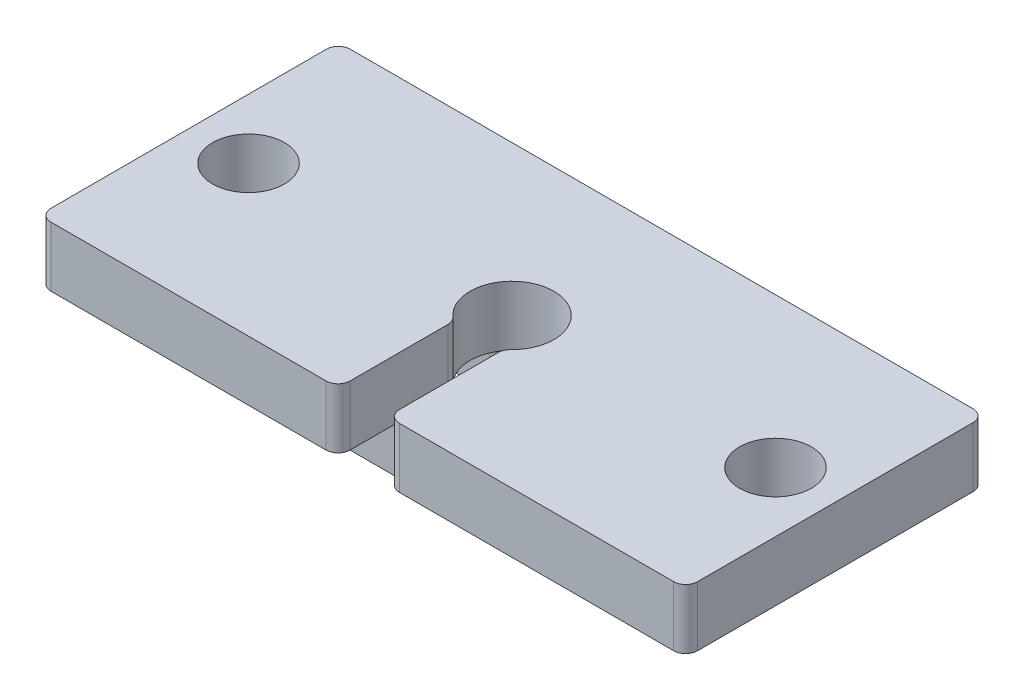
SolidWorks part; units mm, degrees
ref_plane "Front Plane" through (0, 0, 0) normal (0, 0, 1) x (1, 0, 0)
ref_plane "Top Plane" through (0, 0, 0) normal (0, 1, 0) x (1, 0, 0)
ref_plane "Right Plane" through (0, 0, 0) normal (1, 0, 0) x (0, 0, -1)
sketch "Sketch1" plane through (0, 0, 0) normal (0, 1, 0) x (1, 0, 0)
  line L0 (-27.2141, 1.8927) -> (26.7859, 1.8927) construction
  line L1 (-26.2141, 14.3927) -> (25.7859, 14.3927)
  line L2 (-27.2141, 13.3927) -> (-27.2141, -9.6073)
  line L3 (-26.2141, -10.6073) -> (-3.237, -10.6073)
  line L4 (26.7859, 13.3927) -> (26.7859, -9.6073)
  line L5 (-2.237, -1.4408) -> (-2.237, -9.6073)
  line L6 (1.8931, -1.3623) -> (1.8931, -9.6073)
  line L7 (2.8931, -10.6073) -> (25.7859, -10.6073)
  circle A0 centre (-22.2141, 1.8927) radius 3
  circle A1 centre (21.7859, 1.8927) radius 3
  arc A3 (-2.5652, -0.7) -> (2.2026, -0.639) centre (-0.2141, 1.8927) cw
  arc A4 (-2.237, -9.6073) -> (-3.237, -10.6073) centre (-3.237, -9.6073) cw
  arc A5 (2.8931, -10.6073) -> (1.8931, -9.6073) centre (2.8931, -9.6073) cw
  arc A6 (-2.237, -1.4408) -> (-2.5652, -0.7) centre (-3.237, -1.4408) ccw
  arc A7 (1.8931, -1.3623) -> (2.2026, -0.639) centre (2.8931, -1.3623) cw
  arc A8 (25.7859, -10.6073) -> (26.7859, -9.6073) centre (25.7859, -9.6073) ccw
  arc A9 (26.7859, 13.3927) -> (25.7859, 14.3927) centre (25.7859, 13.3927) ccw
  arc A10 (-26.2141, -10.6073) -> (-27.2141, -9.6073) centre (-26.2141, -9.6073) cw
  arc A11 (-27.2141, 13.3927) -> (-26.2141, 14.3927) centre (-26.2141, 13.3927) cw
  point P19 (1.8931, -10.6073)
  point P26 (26.7859, -10.6073)
  point P29 (26.7859, 14.3927)
  point P34 (-27.2141, 14.3927)
  dimension "D3" = 44
  dimension "D5" = 1
  dimension "D6" = 1
  dimension "D7" = 1
  dimension "D8" = 1
  dimension "D9" = 1
  dimension "D1" = 54
  dimension "D2" = 25
  dimension "D4" = 5
extrude "Boss-Extrude1" add sketch "Sketch1" along normal blind 5
sketch3d "3DSketch1"
  line L0 (26.7859, 0, 9.6073) -> (26.7859, 0, -13.3927) construction
  line L5 (25.7859, 0, -14.3927) -> (-26.2141, 0, -14.3927) construction
  line L6 (4.2454, 0, -4.8927) -> (4.2454, 0, -5.8927)
  line L7 (16.5434, 0, -4.3927) -> (4.7454, 0, -4.3927)
  line L8 (16.7859, 0, -9.1503) -> (16.7859, 0, -4.6352)
  line L9 (16.5434, 0, -9.3927) -> (-16.9717, 0, -9.3927)
  line L10 (-17.2141, 0, -9.1503) -> (-17.2141, 0, -4.6352)
  line L14 (-16.9717, 0, -4.3927) -> (-4.5831, 0, -4.3927)
  line L15 (-4.0831, 0, -4.8927) -> (-4.0831, 0, -5.8927)
  line L16 (3.7454, 0, -6.3927) -> (-3.5831, 0, -6.3927)
  line L17 (16.5434, 0, 0.6073) -> (4.2859, 0, 0.6073)
  line L18 (16.7859, 0, 0.8497) -> (16.7859, 0, 5.3648)
  line L20 (-17.2141, 0, 0.8497) -> (-17.2141, 0, 5.3648)
  line L21 (16.5434, 0, 5.6073) -> (2.1355, 0, 5.6073)
  line L22 (3.7859, 0, 1.1073) -> (3.7859, 0, 1.8648)
  line L23 (3.5434, 0, 2.1073) -> (2.3931, 0, 2.1073)
  line L24 (1.8931, 0, 1.3623) -> (1.8931, 0, 9.6073) construction
  line L25 (1.8931, 0, 2.6073) -> (1.8931, 0, 5.3648)
  line L26 (-16.9717, 0, 0.6073) -> (-4.7141, 0, 0.6073)
  line L27 (-4.2141, 0, 1.1073) -> (-4.2141, 0, 1.8648)
  line L28 (-3.9717, 0, 2.1073) -> (-2.737, 0, 2.1073)
  line L29 (-2.237, 0, 9.6073) -> (-2.237, 0, 1.4408) construction
  line L30 (-27.2141, 0, -13.3927) -> (-27.2141, 0, 9.6073) construction
  line L31 (-2.237, 0, 2.6073) -> (-2.237, 0, 5.3648)
  line L32 (-2.4794, 0, 5.6073) -> (-16.9717, 0, 5.6073)
  arc A0 (3.7454, 0, -6.3927) -> (4.2454, 0, -5.8927) centre (3.7454, 0, -5.8927) ccw
  arc A1 (-4.0831, 0, -5.8927) -> (-3.5831, 0, -6.3927) centre (-3.5831, 0, -5.8927) ccw
  arc A2 (-4.5831, 0, -4.3927) -> (-4.0831, 0, -4.8927) centre (-4.5831, 0, -4.8927) ccw
  arc A3 (4.7454, 0, -4.3927) -> (4.2454, 0, -4.8927) centre (4.7454, 0, -4.8927) ccw
  arc A4 (3.7859, 0, 1.1073) -> (4.2859, 0, 0.6073) centre (4.2859, 0, 1.1073) ccw
  arc A5 (1.8931, 0, 2.6073) -> (2.3931, 0, 2.1073) centre (2.3931, 0, 2.6073) ccw
  arc A6 (-2.237, 0, 2.6073) -> (-2.737, 0, 2.1073) centre (-2.737, 0, 2.6073) ccw
  arc A7 (-4.7141, 0, 0.6073) -> (-4.2141, 0, 1.1073) centre (-4.7141, 0, 1.1073) ccw
  arc A8 (-2.237, 0, 5.3648) -> (-2.4794, 0, 5.6073) centre (-2.4794, 0, 5.3648) ccw
  arc A9 (1.8931, 0, 5.3648) -> (2.1355, 0, 5.6073) centre (2.1355, 0, 5.3648) ccw
  arc A10 (16.7859, 0, -9.1503) -> (16.5434, 0, -9.3927) centre (16.5434, 0, -9.1503) ccw
  arc A11 (16.5434, 0, -4.3927) -> (16.7859, 0, -4.6352) centre (16.5434, 0, -4.6352) ccw
  arc A12 (-17.2141, 0, -9.1503) -> (-16.9717, 0, -9.3927) centre (-16.9717, 0, -9.1503) ccw
  arc A13 (-16.9717, 0, -4.3927) -> (-17.2141, 0, -4.6352) centre (-16.9717, 0, -4.6352) ccw
  arc A14 (-17.2141, 0, 0.8497) -> (-16.9717, 0, 0.6073) centre (-16.9717, 0, 0.8497) ccw
  arc A15 (-16.9717, 0, 5.6073) -> (-17.2141, 0, 5.3648) centre (-16.9717, 0, 5.3648) ccw
  arc A16 (16.7859, 0, 5.3648) -> (16.5434, 0, 5.6073) centre (16.5434, 0, 5.3648) ccw
  arc A17 (16.7859, 0, 0.8497) -> (16.5434, 0, 0.6073) centre (16.5434, 0, 0.8497) ccw
  arc A18 (3.5434, 0, 2.1073) -> (3.7859, 0, 1.8648) centre (3.5434, 0, 1.8648) ccw
  arc A19 (-3.9717, 0, 2.1073) -> (-4.2141, 0, 1.8648) centre (-3.9717, 0, 1.8648) ccw
  point P14 (4.2454, 0, -6.3927)
  point P15 (3.7454, -0.5, -5.8927)
  point P18 (-4.0831, 0, -6.3927)
  point P19 (-3.5831, -0.5, -5.8927)
  point P22 (-4.0831, 0, -4.3927)
  point P23 (-4.5831, 0.5, -4.8927)
  point P26 (4.2454, 0, -4.3927)
  point P27 (4.7454, -0.5, -4.8927)
  point P48 (3.7859, 0, 0.6073)
  point P49 (4.2859, -0.5, 1.1073)
  point P52 (1.8931, 0, 2.1073)
  point P53 (2.3931, -0.5, 2.6073)
  point P56 (-2.237, 0, 2.1073)
  point P57 (-2.737, 0.5, 2.6073)
  point P60 (-4.2141, 0, 0.6073)
  point P61 (-4.7141, -0.5, 1.1073)
  point P64 (-2.237, 0, 5.6073)
  point P65 (-2.4794, -0.2424, 5.3648)
  point P68 (1.8931, 0, 5.6073)
  point P69 (2.1355, 0.2424, 5.3648)
  point P72 (16.7859, 0, -9.3927)
  point P73 (16.5434, 0.2424, -9.1503)
  point P76 (16.7859, 0, -4.3927)
  point P77 (16.5434, 0.2424, -4.6352)
  point P80 (-17.2141, 0, -9.3927)
  point P81 (-16.9717, -0.2424, -9.1503)
  point P84 (-17.2141, 0, -4.3927)
  point P85 (-16.9717, -0.2424, -4.6352)
  point P88 (-17.2141, 0, 0.6073)
  point P89 (-16.9717, -0.2424, 0.8497)
  point P92 (-17.2141, 0, 5.6073)
  point P93 (-16.9717, -0.2424, 5.3648)
  point P96 (16.7859, 0, 5.6073)
  point P97 (16.5434, -0.2424, 5.3648)
  point P100 (16.7859, 0, 0.6073)
  point P101 (16.5434, 0.2424, 0.8497)
  point P104 (3.7859, 0, 2.1073)
  point P105 (3.5434, 0.2424, 1.8648)
  point P108 (-4.2141, 0, 2.1073)
  point P109 (-3.9717, -0.2424, 1.8648)
  dimension "D4" = 0.5
  dimension "D5" = 0.5
  dimension "D6" = 0.5
  dimension "D7" = 0.5
  dimension "D11" = 0.5
  dimension "D12" = 0.5
  dimension "D13" = 0.5
  dimension "D14" = 0.5
  dimension "D15" = 0.2424
  dimension "D16" = 0.2424
  dimension "D17" = 0.2424
  dimension "D18" = 0.2424
  dimension "D19" = 0.2424
  dimension "D20" = 0.2424
  dimension "D21" = 0.2424
  dimension "D22" = 0.2424
  dimension "D23" = 0.2424
  dimension "D24" = 0.2424
  dimension "D25" = 0.2424
  dimension "D26" = 0.2424
  dimension "D1" = 34
  dimension "D2" = 10
  dimension "D3" = 5
  dimension "D8" = 10
  dimension "D9" = 34
  dimension "D10" = 10
extrude "Boss-Extrude2" add sketch "3DSketch1" along direction (0, -1, 0) on the side against the normal blind 4
